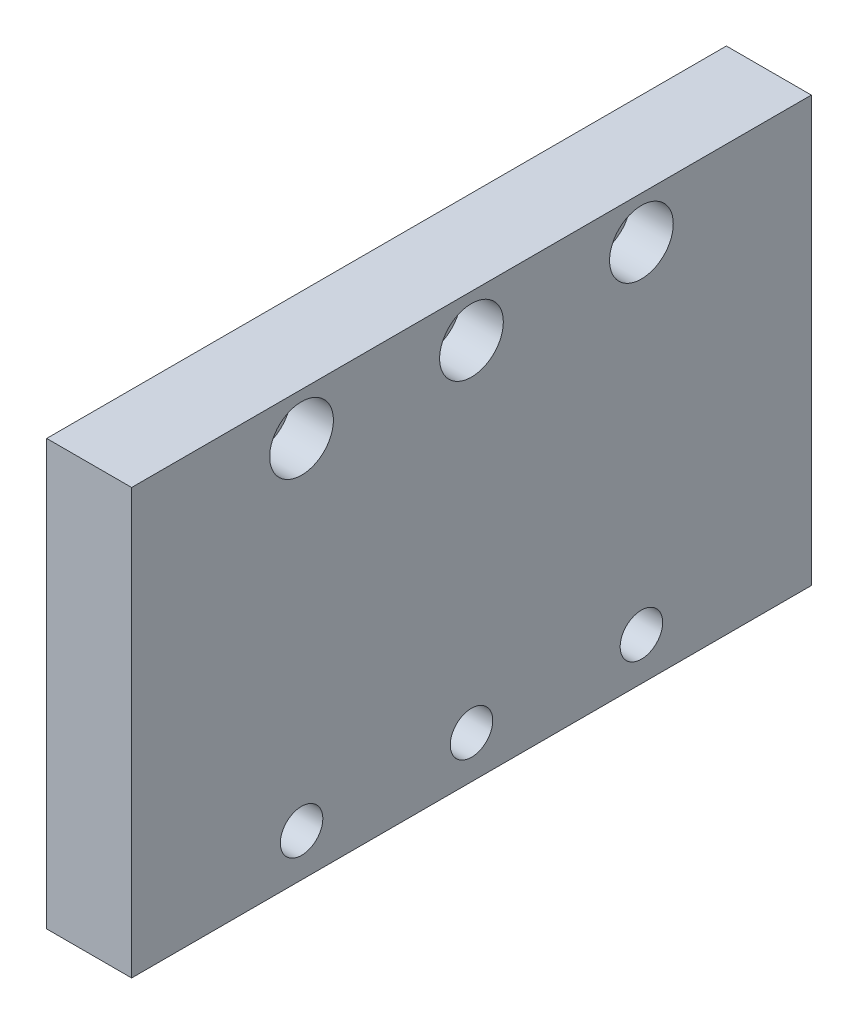
SolidWorks part; units mm, degrees
material "6061 Alloy"
ref_plane "Front" through (0, 0, 0) normal (0, 0, 1) x (1, 0, 0)
ref_plane "Top" through (0, 0, 0) normal (0, 1, 0) x (1, 0, 0)
ref_plane "Right" through (0, 0, 0) normal (1, 0, 0) x (0, 0, -1)
sketch "Sketch2" plane through (0, 0, 0) normal (0, 0, 1) x (1, 0, 0)
  line L7 (-6.35, 31.75) -> (6.35, 31.75)
  line L9 (6.35, -19.05) -> (6.35, -31.75)
  line L10 (6.35, 31.75) -> (6.35, -19.05)
  line L11 (-6.35, 31.75) -> (-6.35, 19.05)
  line L14 (-6.35, 19.05) -> (-6.35, -31.75)
  line L15 (-6.35, -31.75) -> (6.35, -31.75)
  dimension "D1" = 12.7
  dimension "D2" = 63.5
  dimension "D3" = 12.7
  dimension "D4" = 12.7
  dimension "D5" = 31.75
  dimension "D6" = 6.35
extrude "Boss-Extrude1" add sketch "Sketch2" along normal mid plane 101.6
hole_wizard "1/4\"-20 threaded c-bore" positions "Sketch4" profile "Sketch5" counterbore size "#10" standard "ANSI Inch" end condition through all
sketch "Sketch4" plane through (-6.35, 0, 0) normal (-1, 0, 0) x (0, 0, 1)
  line L0 (50.8, -31.75) -> (-50.8, -31.75) construction
  point P0 (-25.4, -25.4)
  point P2 (0, -25.4)
  point P4 (25.4, -25.4)
  point P10 (0, -31.75)
  dimension "D1" = 25.4
  dimension "D2" = 25.4
  dimension "D3" = 6.35
sketch "Sketch5" plane through (-6.35, -25.4, -25.4) normal (0, 1, 0) x (0, 0, 1)
  line L0 (0, 0) -> (0, 12.7)
  line L1 (0, 12.7) -> (3.175, 12.7)
  line L3 (3.175, 12.7) -> (3.175, 6.35)
  line L4 (3.175, 6.35) -> (4.7625, 6.35)
  line L5 (4.7625, 6.35) -> (4.7625, 0)
  line L7 (4.7625, 0) -> (0, 0)
  line L11 (0, -6.35) -> (0, 107.95) construction
  dimension "Thru Hole Dia." = 6.35
  dimension "Thru Hole Depth" = 12.7
  dimension "C'Bore Dia." = 9.525
  dimension "C'Bore Depth" = 6.35
hole_wizard "1/4\"-20 threaded c-bore opposite" positions "Sketch7" profile "Sketch6" counterbore size "#10" standard "ANSI Inch" end condition through all
sketch "Sketch7" plane through (6.35, 0, 0) normal (1, 0, 0) x (0, 0, -1)
  line L0 (-50.8, 31.75) -> (50.8, 31.75) construction
  point P0 (-25.4, 25.4)
  point P2 (0, 25.4)
  point P4 (25.4, 25.4)
  dimension "D1" = 6.35
  dimension "D2" = 25.4
  dimension "D3" = 25.4
sketch "Sketch6" plane through (6.35, 25.4, 25.4) normal (0, 1, 0) x (0, 0, -1)
  line L0 (0, 0) -> (0, 12.7)
  line L1 (0, 12.7) -> (3.175, 12.7)
  line L3 (3.175, 12.7) -> (3.175, 6.35)
  line L4 (3.175, 6.35) -> (4.7625, 6.35)
  line L5 (4.7625, 6.35) -> (4.7625, 0)
  line L7 (4.7625, 0) -> (0, 0)
  line L11 (0, -6.35) -> (0, 107.95) construction
  dimension "Thru Hole Dia." = 6.35
  dimension "Thru Hole Depth" = 12.7
  dimension "C'Bore Dia." = 9.525
  dimension "C'Bore Depth" = 6.35
